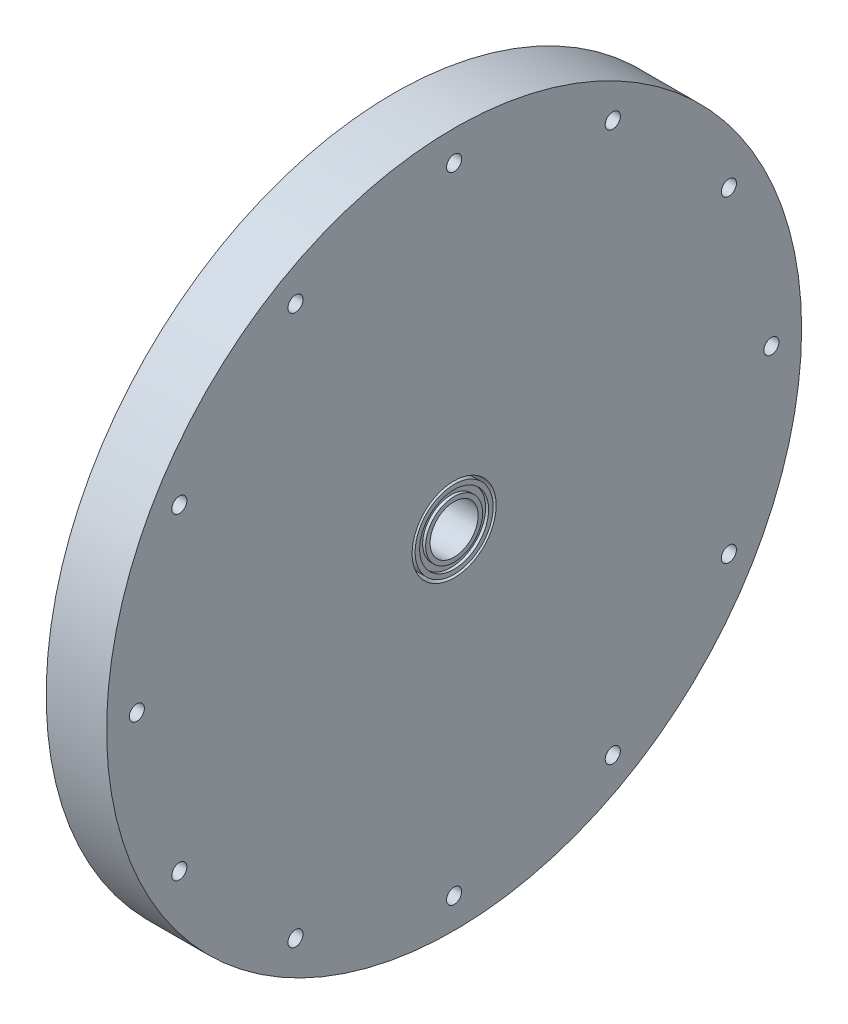
SolidWorks part; units mm, degrees
ref_plane "Front Plane" through (0, 0, 0) normal (0, 0, 1) x (1, 0, 0)
ref_plane "Top Plane" through (0, 0, 0) normal (0, 1, 0) x (1, 0, 0)
ref_plane "Right Plane" through (0, 0, 0) normal (1, 0, 0) x (0, 0, -1)
sketch "Sketch1" plane through (0, 0, 0) normal (1, 0, 0) x (0, 0, -1)
  circle A0 centre (0, 0) radius 146.05
  dimension "D1" = 292.1
extrude "Boss-Extrude1" add sketch "Sketch1" along normal blind 25.4 contours A0
sketch "Sketch2" plane through (0, 0, 0) normal (-1, 0, 0) x (0, 0, 1)
  circle A0 centre (0, 0) radius 18.9382
  dimension "D1" = 37.8765
extrude "Boss-Extrude2" add sketch "Sketch2" along normal blind 50.8 contours A0
sketch "Sketch3" plane through (-50.8, 0, 0) normal (-1, 0, 0) x (0, 0, 1)
  line L0 (-18.9382, 0) -> (18.9382, 0) construction
  line L1 (-18.9382, 0) -> (18.9382, 0)
  arc A2 (18.9382, 0) -> (-18.9382, 0) centre (0, 0) ccw
revolve "Revolve1" add sketch "Sketch3" angle 360 about L0
sketch "Sketch4" plane through (25.4, 0, 0) normal (1, 0, 0) x (0, 0, -1)
  line L0 (0, 0) -> (0, -146.05) construction
  line L1 (0, 0) -> (0, -133.35) construction
  circle A0 centre (0, 0) radius 146.05 construction
  circle A1 centre (0, -133.35) radius 3.175
  circle A9 centre (-66.675, -115.4845) radius 3.175
  circle A10 centre (-115.4845, -66.675) radius 3.175
  circle A11 centre (-133.35, 0) radius 3.175
  circle A12 centre (-115.4845, 66.675) radius 3.175
  circle A13 centre (-66.675, 115.4845) radius 3.175
  circle A14 centre (0, 133.35) radius 3.175
  circle A15 centre (66.675, 115.4845) radius 3.175
  circle A16 centre (115.4845, 66.675) radius 3.175
  circle A17 centre (133.35, 0) radius 3.175
  circle A18 centre (115.4845, -66.675) radius 3.175
  circle A19 centre (66.675, -115.4845) radius 3.175
  point P24 (0, 0)
  dimension "D1" = 6.35
  dimension "D3" = 133.35
  dimension "D4" = 133.35
  dimension "D2" = 12
extrude "Cut-Extrude1" cut sketch "Sketch4" against normal blind 25.4
sketch "Sketch5" plane through (25.4, 0, 0) normal (1, 0, 0) x (0, 0, -1)
  circle A0 centre (0, 0) radius 18.9382
  dimension "D1" = 37.8765
extrude "Cut-Extrude2" cut sketch "Sketch5" against normal blind 6.35
sketch "Sketch6" plane through (0, 0, 0) normal (-1, 0, 0) x (0, 0, 1)
  circle A0 centre (0, 0) radius 16.3982
  circle A2 centre (0, 0) radius 17.6682
  dimension "D1" = 32.7965
  dimension "D2" = 35.3365
extrude "Cut-Extrude4" cut sketch "Sketch6" along normal blind 50.8 and the other way blind 33.02
sketch "Sketch7" plane through (19.05, 0, 0) normal (1, 0, 0) x (0, 0, -1)
  circle A0 centre (0, 0) radius 10.1102
extrude "Cut-Extrude5" cut sketch "Sketch7" against normal blind 83.82
sketch "Sketch8" plane through (0, 0, 0) normal (0, 0, 1) x (1, 0, 0)
  circle A0 centre (-57.2783, 3.6753) radius 1.0787
extrude "Cut-Extrude6" cut sketch "Sketch8" against normal blind 25.4
pattern_circular "CirPattern1" count 9 over 360 about axis through (-50.8, 0, 0) along (-1, 0, 0) of "Cut-Extrude6"
sketch "Sketch9" plane through (19.05, 0, 0) normal (1, 0, 0) x (0, 0, -1)
  circle A2 centre (0, 0) radius 16.3982
  circle A3 centre (0, 0) radius 16.3982
  circle A5 centre (0, 0) radius 16.3982
  circle A6 centre (0, 0) radius 10.1102
  circle M2 centre (0, 0) radius 10.1102
  circle M3 centre (0, 0) radius 16.3982
  dimension "D1" = 0
extrude "Boss-Extrude3" add sketch "Sketch9" along normal blind 6.35 contours M3 M2
sketch "Sketch10" plane through (19.05, 0, 0) normal (1, 0, 0) x (0, 0, -1)
  circle A0 centre (0, 0) radius 18.9382
  circle A1 centre (0, 0) radius 17.6682
extrude "Boss-Extrude4" add sketch "Sketch10" along normal blind 6.35
sketch "Sketch11" plane through (25.4, 0, 0) normal (1, 0, 0) x (0, 0, -1)
  circle A0 centre (0, 0) radius 11.9532
  circle A1 centre (0, 0) radius 14.4932
  circle A2 centre (0, 0) radius 10.1102 construction
  dimension "D1" = 2.54
  dimension "D2" = 1.843
extrude "Cut-Extrude7" cut sketch "Sketch11" against normal blind 1.27
sketch "Sketch14" plane through (25.4, 0, 0) normal (1, 0, 0) x (0, 0, -1)
  circle A0 centre (0, 0) radius 74.8888
